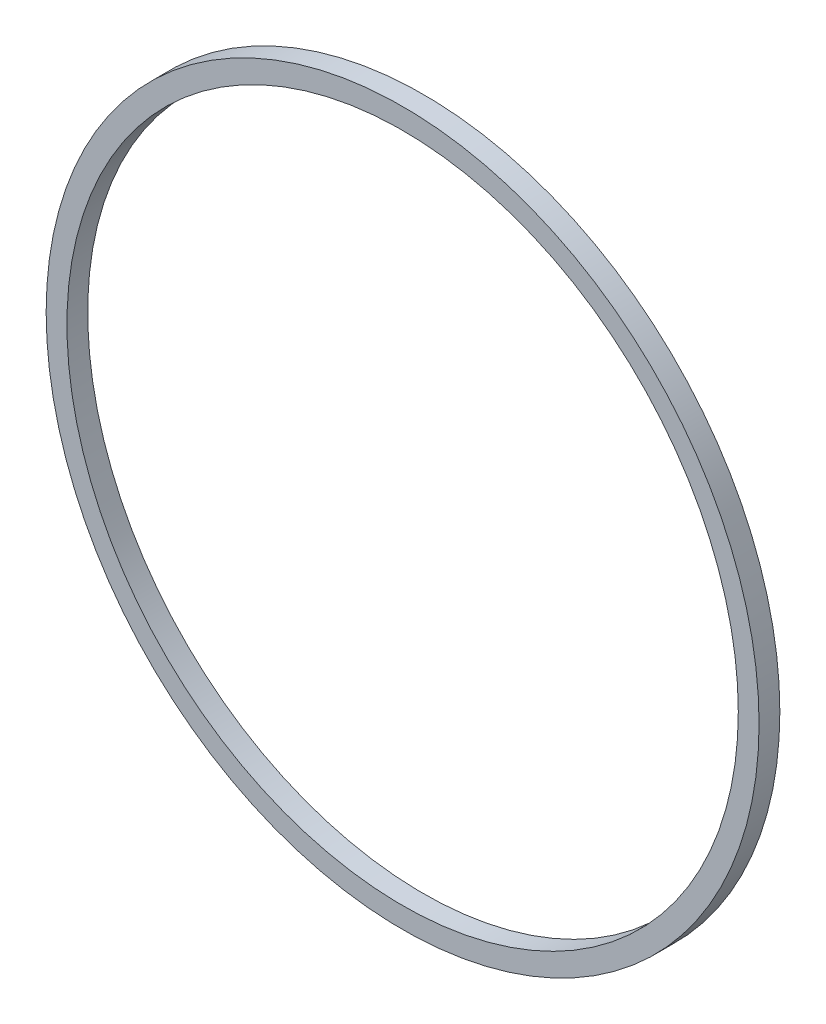
SolidWorks part; units mm, degrees
ref_plane "Front Plane" through (0, 0, 0) normal (0, 0, 1) x (1, 0, 0)
ref_plane "Top Plane" through (0, 0, 0) normal (0, 1, 0) x (1, 0, 0)
ref_plane "Right Plane" through (0, 0, 0) normal (1, 0, 0) x (0, 0, -1)
sketch "Sketch1" plane through (0, 0, 0) normal (0, 0, 1) x (1, 0, 0)
  circle A0 centre (0, 0) radius 30.5054
  circle A1 centre (0, 0) radius 28.7274
  dimension "D1" = 61.0108
  dimension "D2" = 1.778
extrude "Boss-Extrude1" add sketch "Sketch1" along normal blind 1.778
